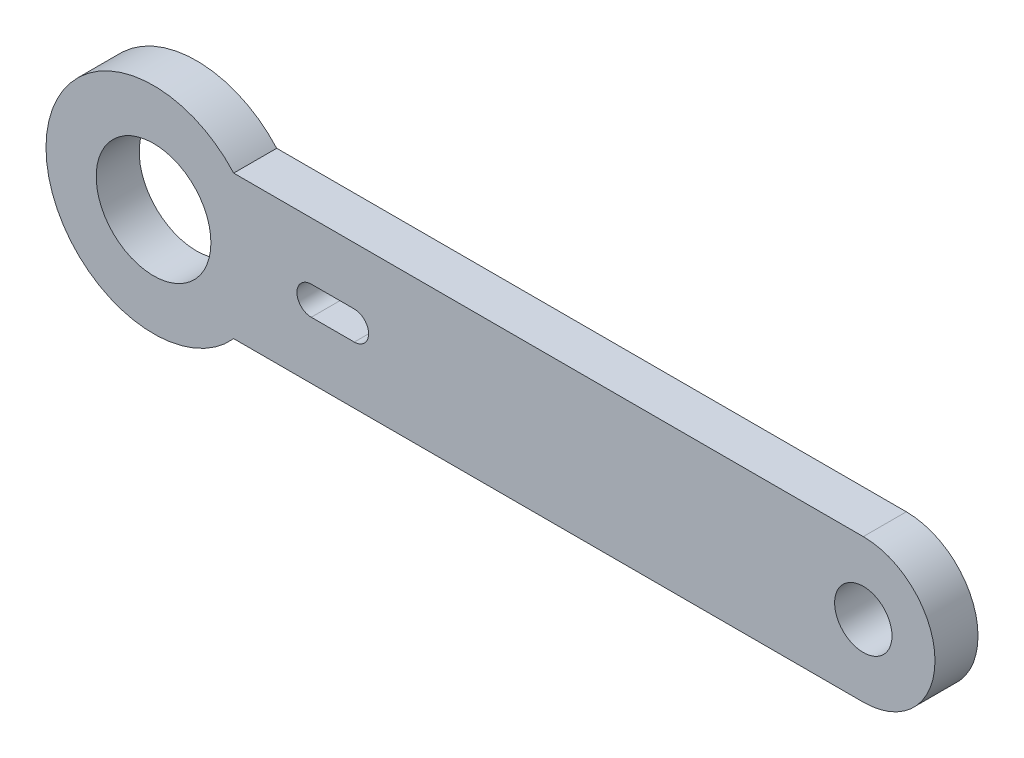
SolidWorks part; units mm, degrees
ref_plane "前视基准面" through (0, 0, 0) normal (0, 0, 1) x (1, 0, 0)
ref_plane "上视基准面" through (0, 0, 0) normal (0, 1, 0) x (1, 0, 0)
ref_plane "右视基准面" through (0, 0, 0) normal (1, 0, 0) x (0, 0, -1)
sketch "草图1" plane through (0, 0, 0) normal (0, 0, 1) x (1, 0, 0)
  line L0 (0, 0) -> (49.5, 0) construction
  line L1 (55, 0) -> (-55, 0) construction
  line L2 (5.5902, 5) -> (49.5, 5)
  line L3 (5.5902, -5) -> (49.5, -5)
  line L4 (11, 0) -> (14, 0) construction
  line L5 (11, 1) -> (14, 1)
  line L6 (11, -1) -> (14, -1)
  arc A1 (49.5, -5) -> (49.5, 5) centre (49.5, 0) ccw
  arc A2 (5.5902, 5) -> (5.5902, -5) centre (0, 0) ccw
  circle A3 centre (0, 0) radius 4
  circle A4 centre (49.5, 0) radius 2
  arc A5 (11, 1) -> (11, -1) centre (11, 0) ccw
  arc A6 (14, -1) -> (14, 1) centre (14, 0) ccw
  point P5 (24.75, 0)
  point P16 (12.5, 0)
  point P21 (10, 0)
  dimension "D1" = 10
extrude "凸台-拉伸1" add sketch "草图1" along normal mid plane 3
